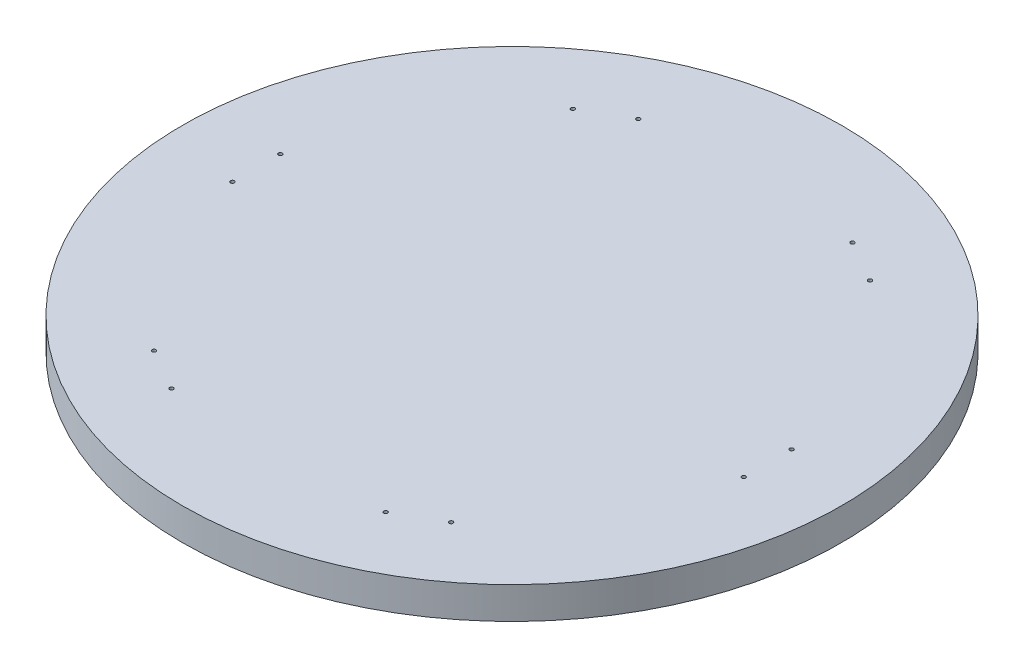
SolidWorks part; units mm, degrees
ref_plane "Front Plane" through (0, 0, 0) normal (0, 0, 1) x (1, 0, 0)
ref_plane "Top Plane" through (0, 0, 0) normal (0, 1, 0) x (1, 0, 0)
ref_plane "Right Plane" through (0, 0, 0) normal (1, 0, 0) x (0, 0, -1)
sketch "Sketch1" plane through (0, 0, 0) normal (0, 1, 0) x (1, 0, 0)
  circle A0 centre (0, 0) radius 261.9375
extrude "Boss-Extrude1" add sketch "Sketch1" along normal blind 25.4
sketch "Sketch6" plane through (0, 0, 0) normal (0, -1, 0) x (1, 0, 0)
  line L0 (203.2, 19.05) -> (203.2, -19.05) construction
  line L1 (215.9, 19.05) -> (215.9, -19.05)
  line L2 (190.5, 19.05) -> (190.5, -19.05)
  line L3 (203.2, -16.5451) -> (201.0307, -17.7976) construction
  line L4 (201.0307, -17.7976) -> (201.0307, -20.3024) construction
  line L5 (201.0307, -20.3024) -> (203.2, -21.5549) construction
  line L6 (203.2, -21.5549) -> (205.3693, -20.3024) construction
  line L7 (205.3693, -20.3024) -> (205.3693, -17.7976) construction
  line L8 (205.3693, -17.7976) -> (203.2, -16.5451) construction
  line L9 (203.2, 22.1294) -> (201.0307, 20.8769) construction
  line L10 (201.0307, 20.8769) -> (201.0307, 18.372) construction
  line L11 (201.0307, 18.372) -> (203.2, 17.1196) construction
  line L12 (203.2, 17.1196) -> (205.3693, 18.372) construction
  line L13 (205.3693, 18.372) -> (205.3693, 20.8769) construction
  line L14 (205.3693, 20.8769) -> (203.2, 22.1294) construction
  line L15 (0, 0) -> (203.2, 0) construction
  line L16 (87.2715, -184.2489) -> (85.1022, -182.9965) construction
  line L17 (85.1022, -182.9965) -> (82.9329, -184.2489) construction
  line L18 (82.9329, -184.2489) -> (82.9329, -186.7538) construction
  line L19 (82.9329, -186.7538) -> (85.1022, -188.0063) construction
  line L20 (85.1022, -188.0063) -> (87.2715, -186.7538) construction
  line L21 (87.2715, -186.7538) -> (87.2715, -184.2489) construction
  line L22 (120.7646, -164.9117) -> (118.5953, -163.6592) construction
  line L23 (118.5953, -163.6592) -> (116.426, -164.9117) construction
  line L24 (116.426, -164.9117) -> (116.426, -167.4166) construction
  line L25 (116.426, -167.4166) -> (118.5953, -168.669) construction
  line L26 (118.5953, -168.669) -> (120.7646, -167.4166) construction
  line L27 (120.7646, -167.4166) -> (120.7646, -164.9117) construction
  line L28 (0, 0) -> (101.6, -175.9764) construction
  line L29 (118.0978, -166.4514) -> (85.1022, -185.5014) construction
  line L30 (124.4478, -177.4499) -> (91.4522, -196.4999)
  line L31 (111.7478, -155.4528) -> (78.7522, -174.5028)
  line L32 (-115.9285, -167.7038) -> (-115.9285, -165.1989) construction
  line L33 (-115.9285, -165.1989) -> (-118.0978, -163.9465) construction
  line L34 (-118.0978, -163.9465) -> (-120.2671, -165.1989) construction
  line L35 (-120.2671, -165.1989) -> (-120.2671, -167.7038) construction
  line L36 (-120.2671, -167.7038) -> (-118.0978, -168.9563) construction
  line L37 (-118.0978, -168.9563) -> (-115.9285, -167.7038) construction
  line L38 (-82.4354, -187.0411) -> (-82.4354, -184.5362) construction
  line L39 (-82.4354, -184.5362) -> (-84.6047, -183.2837) construction
  line L40 (-84.6047, -183.2837) -> (-86.774, -184.5362) construction
  line L41 (-86.774, -184.5362) -> (-86.774, -187.0411) construction
  line L42 (-86.774, -187.0411) -> (-84.6047, -188.2935) construction
  line L43 (-84.6047, -188.2935) -> (-82.4354, -187.0411) construction
  line L44 (0, 0) -> (-101.6, -175.9764) construction
  line L45 (-85.1022, -185.5014) -> (-118.0978, -166.4514) construction
  line L46 (-91.4522, -196.4999) -> (-124.4478, -177.4499)
  line L47 (-78.7522, -174.5028) -> (-111.7478, -155.4528)
  line L48 (-203.2, 16.5451) -> (-201.0307, 17.7976) construction
  line L49 (-201.0307, 17.7976) -> (-201.0307, 20.3024) construction
  line L50 (-201.0307, 20.3024) -> (-203.2, 21.5549) construction
  line L51 (-203.2, 21.5549) -> (-205.3693, 20.3024) construction
  line L52 (-205.3693, 20.3024) -> (-205.3693, 17.7976) construction
  line L53 (-205.3693, 17.7976) -> (-203.2, 16.5451) construction
  line L54 (-203.2, -22.1294) -> (-201.0307, -20.8769) construction
  line L55 (-201.0307, -20.8769) -> (-201.0307, -18.372) construction
  line L56 (-201.0307, -18.372) -> (-203.2, -17.1196) construction
  line L57 (-203.2, -17.1196) -> (-205.3693, -18.372) construction
  line L58 (-205.3693, -18.372) -> (-205.3693, -20.8769) construction
  line L59 (-205.3693, -20.8769) -> (-203.2, -22.1294) construction
  line L60 (0, 0) -> (-203.2, 0) construction
  line L61 (-203.2, -19.05) -> (-203.2, 19.05) construction
  line L62 (-215.9, -19.05) -> (-215.9, 19.05)
  line L63 (-190.5, -19.05) -> (-190.5, 19.05)
  line L64 (-87.2715, 184.2489) -> (-85.1022, 182.9965) construction
  line L65 (-85.1022, 182.9965) -> (-82.9329, 184.2489) construction
  line L66 (-82.9329, 184.2489) -> (-82.9329, 186.7538) construction
  line L67 (-82.9329, 186.7538) -> (-85.1022, 188.0063) construction
  line L68 (-85.1022, 188.0063) -> (-87.2715, 186.7538) construction
  line L69 (-87.2715, 186.7538) -> (-87.2715, 184.2489) construction
  line L70 (-120.7646, 164.9117) -> (-118.5953, 163.6592) construction
  line L71 (-118.5953, 163.6592) -> (-116.426, 164.9117) construction
  line L72 (-116.426, 164.9117) -> (-116.426, 167.4166) construction
  line L73 (-116.426, 167.4166) -> (-118.5953, 168.669) construction
  line L74 (-118.5953, 168.669) -> (-120.7646, 167.4166) construction
  line L75 (-120.7646, 167.4166) -> (-120.7646, 164.9117) construction
  line L76 (0, 0) -> (-101.6, 175.9764) construction
  line L77 (-118.0978, 166.4514) -> (-85.1022, 185.5014) construction
  line L78 (-124.4478, 177.4499) -> (-91.4522, 196.4999)
  line L79 (-111.7478, 155.4528) -> (-78.7522, 174.5028)
  line L80 (115.9285, 167.7038) -> (115.9285, 165.1989) construction
  line L81 (115.9285, 165.1989) -> (118.0978, 163.9465) construction
  line L82 (118.0978, 163.9465) -> (120.2671, 165.1989) construction
  line L83 (120.2671, 165.1989) -> (120.2671, 167.7038) construction
  line L84 (120.2671, 167.7038) -> (118.0978, 168.9563) construction
  line L85 (118.0978, 168.9563) -> (115.9285, 167.7038) construction
  line L86 (82.4354, 187.0411) -> (82.4354, 184.5362) construction
  line L87 (82.4354, 184.5362) -> (84.6047, 183.2837) construction
  line L88 (84.6047, 183.2837) -> (86.774, 184.5362) construction
  line L89 (86.774, 184.5362) -> (86.774, 187.0411) construction
  line L90 (86.774, 187.0411) -> (84.6047, 188.2935) construction
  line L91 (84.6047, 188.2935) -> (82.4354, 187.0411) construction
  line L92 (0, 0) -> (101.6, 175.9764) construction
  line L93 (85.1022, 185.5014) -> (118.0978, 166.4514) construction
  line L94 (91.4522, 196.4999) -> (124.4478, 177.4499)
  line L95 (78.7522, 174.5028) -> (111.7478, 155.4528)
  arc A0 (215.9, 19.05) -> (190.5, 19.05) centre (203.2, 19.05) ccw
  arc A1 (190.5, -19.05) -> (215.9, -19.05) centre (203.2, -19.05) ccw
  circle A2 centre (203.2, -19.05) radius 2.1693 construction
  circle A3 centre (203.2, 19.6245) radius 2.1693 construction
  circle A4 centre (203.2, -19.05) radius 1.524 construction
  circle A5 centre (203.2, 19.6245) radius 1.524 construction
  circle A6 centre (85.1022, -185.5014) radius 2.1693 construction
  circle A7 centre (118.5953, -166.1641) radius 2.1693 construction
  circle A8 centre (85.1022, -185.5014) radius 1.524 construction
  circle A9 centre (118.5953, -166.1641) radius 1.524 construction
  arc A10 (124.4478, -177.4499) -> (111.7478, -155.4528) centre (118.0978, -166.4514) ccw
  arc A11 (78.7522, -174.5028) -> (91.4522, -196.4999) centre (85.1022, -185.5014) ccw
  circle A12 centre (-118.0978, -166.4514) radius 2.1693 construction
  circle A13 centre (-84.6047, -185.7886) radius 2.1693 construction
  circle A14 centre (-118.0978, -166.4514) radius 1.524 construction
  circle A15 centre (-84.6047, -185.7886) radius 1.524 construction
  arc A16 (-91.4522, -196.4999) -> (-78.7522, -174.5028) centre (-85.1022, -185.5014) ccw
  arc A17 (-111.7478, -155.4528) -> (-124.4478, -177.4499) centre (-118.0978, -166.4514) ccw
  circle A18 centre (-203.2, 19.05) radius 2.1693 construction
  circle A19 centre (-203.2, -19.6245) radius 2.1693 construction
  circle A20 centre (-203.2, 19.05) radius 1.524 construction
  circle A21 centre (-203.2, -19.6245) radius 1.524 construction
  arc A22 (-215.9, -19.05) -> (-190.5, -19.05) centre (-203.2, -19.05) ccw
  arc A23 (-190.5, 19.05) -> (-215.9, 19.05) centre (-203.2, 19.05) ccw
  circle A24 centre (-85.1022, 185.5014) radius 2.1693 construction
  circle A25 centre (-118.5953, 166.1641) radius 2.1693 construction
  circle A26 centre (-85.1022, 185.5014) radius 1.524 construction
  circle A27 centre (-118.5953, 166.1641) radius 1.524 construction
  arc A28 (-124.4478, 177.4499) -> (-111.7478, 155.4528) centre (-118.0978, 166.4514) ccw
  arc A29 (-78.7522, 174.5028) -> (-91.4522, 196.4999) centre (-85.1022, 185.5014) ccw
  circle A30 centre (118.0978, 166.4514) radius 2.1693 construction
  circle A31 centre (84.6047, 185.7886) radius 2.1693 construction
  circle A32 centre (118.0978, 166.4514) radius 1.524 construction
  circle A33 centre (84.6047, 185.7886) radius 1.524 construction
  arc A34 (91.4522, 196.4999) -> (78.7522, 174.5028) centre (85.1022, 185.5014) ccw
  arc A35 (111.7478, 155.4528) -> (124.4478, 177.4499) centre (118.0978, 166.4514) ccw
  point P2 (203.2, 0)
  point P32 (101.6, -175.9764)
  point P58 (-101.6, -175.9764)
  point P84 (-203.2, 0)
  point P110 (-101.6, 175.9764)
  point P136 (101.6, 175.9764)
  point P160 (0, 0)
  dimension "D1" = 6
extrude "Cut-Extrude4" cut sketch "Sketch6" against normal blind 12.7
sketch "Sketch9" plane through (0, 0, 0) normal (0, -1, 0) x (1, 0, 0)
  circle A0 centre (0, 0) radius 25.4
extrude "Boss-Extrude2" add sketch "Sketch9" along normal blind 10.16 and the other way through all
sketch "Sketch10" plane through (0, -10.16, 0) normal (0, -1, 0) x (1, 0, 0)
  line L0 (0, -2.032) -> (0, 1.524) construction
  line L1 (-1.344, 1.524) -> (1.344, 1.524)
  line L2 (-2.032, 0) -> (-2.032, 1.524)
  line L3 (-2.032, 1.524) -> (-1.344, 1.524)
  line L4 (2.032, 0) -> (2.032, 1.524)
  line L5 (2.032, 1.524) -> (1.344, 1.524)
  arc A0 (-2.032, 0) -> (2.032, 0) centre (0, 0) ccw
extrude "Cut-Extrude7" cut sketch "Sketch10" against normal blind 19.05
sketch "Sketch11" plane through (0, 0, 0) normal (0, -1, 0) x (1, 0, 0)
  line L0 (0, 0) -> (-11.1642, -177.4492) construction
  line L1 (0, 0) -> (0, -291.8902) construction
  line L2 (0, 0) -> (11.1642, -177.4492) construction
  line L3 (-33.3164, -174.6507) -> (-22.2403, -176.0499) construction
  line L4 (-11.1642, -177.4492) -> (0, -177.4492) construction
  line L5 (0, -177.4492) -> (11.1642, -177.4492) construction
  line L6 (-22.2403, -176.0499) -> (-11.1642, -177.4492) construction
  line L7 (-54.9432, -169.0978) -> (-44.1298, -171.8743) construction
  line L8 (-44.1298, -171.8743) -> (-33.3164, -174.6507) construction
  line L9 (-75.7036, -160.8782) -> (-65.3234, -164.988) construction
  line L10 (-65.3234, -164.988) -> (-54.9432, -169.0978) construction
  line L11 (-95.27, -150.1215) -> (-85.4868, -155.4999) construction
  line L12 (-85.4868, -155.4999) -> (-75.7036, -160.8782) construction
  line L13 (-113.334, -136.9973) -> (-104.302, -143.5594) construction
  line L14 (-104.302, -143.5594) -> (-95.27, -150.1215) construction
  line L15 (-129.6106, -121.7125) -> (-121.4723, -129.3549) construction
  line L16 (-121.4723, -129.3549) -> (-113.334, -136.9973) construction
  line L17 (-143.8432, -104.5082) -> (-136.7269, -113.1103) construction
  line L18 (-136.7269, -113.1103) -> (-129.6106, -121.7125) construction
  line L19 (-155.8073, -85.6558) -> (-149.8253, -95.082) construction
  line L20 (-149.8253, -95.082) -> (-143.8432, -104.5082) construction
  line L21 (-165.3143, -65.4525) -> (-160.5608, -75.5542) construction
  line L22 (-160.5608, -75.5542) -> (-155.8073, -85.6558) construction
  line L23 (-172.2141, -44.2171) -> (-168.7642, -54.8348) construction
  line L24 (-168.7642, -54.8348) -> (-165.3143, -65.4525) construction
  line L25 (-176.398, -22.2842) -> (-174.306, -33.2507) construction
  line L26 (-174.306, -33.2507) -> (-172.2141, -44.2171) construction
  line L27 (-177.8, 0) -> (-177.099, -11.1421) construction
  line L28 (-177.099, -11.1421) -> (-176.398, -22.2842) construction
  line L29 (-176.398, 22.2842) -> (-177.099, 11.1421) construction
  line L30 (-177.099, 11.1421) -> (-177.8, 0) construction
  line L31 (-172.2141, 44.2171) -> (-174.306, 33.2507) construction
  line L32 (-174.306, 33.2507) -> (-176.398, 22.2842) construction
  line L33 (-165.3143, 65.4525) -> (-168.7642, 54.8348) construction
  line L34 (-168.7642, 54.8348) -> (-172.2141, 44.2171) construction
  line L35 (-155.8073, 85.6558) -> (-160.5608, 75.5542) construction
  line L36 (-160.5608, 75.5542) -> (-165.3143, 65.4525) construction
  line L37 (-143.8432, 104.5082) -> (-149.8253, 95.082) construction
  line L38 (-149.8253, 95.082) -> (-155.8073, 85.6558) construction
  line L39 (-129.6106, 121.7125) -> (-136.7269, 113.1103) construction
  line L40 (-136.7269, 113.1103) -> (-143.8432, 104.5082) construction
  line L41 (-113.334, 136.9973) -> (-121.4723, 129.3549) construction
  line L42 (-121.4723, 129.3549) -> (-129.6106, 121.7125) construction
  line L43 (-95.27, 150.1215) -> (-104.302, 143.5594) construction
  line L44 (-104.302, 143.5594) -> (-113.334, 136.9973) construction
  line L45 (-75.7036, 160.8782) -> (-85.4868, 155.4999) construction
  line L46 (-85.4868, 155.4999) -> (-95.27, 150.1215) construction
  line L47 (-54.9432, 169.0978) -> (-65.3234, 164.988) construction
  line L48 (-65.3234, 164.988) -> (-75.7036, 160.8782) construction
  line L49 (-33.3164, 174.6507) -> (-44.1298, 171.8743) construction
  line L50 (-44.1298, 171.8743) -> (-54.9432, 169.0978) construction
  line L51 (-11.1642, 177.4492) -> (-22.2403, 176.0499) construction
  line L52 (-22.2403, 176.0499) -> (-33.3164, 174.6507) construction
  line L53 (11.1642, 177.4492) -> (0, 177.4492) construction
  line L54 (0, 177.4492) -> (-11.1642, 177.4492) construction
  line L55 (33.3164, 174.6507) -> (22.2403, 176.0499) construction
  line L56 (22.2403, 176.0499) -> (11.1642, 177.4492) construction
  line L57 (54.9432, 169.0978) -> (44.1298, 171.8743) construction
  line L58 (44.1298, 171.8743) -> (33.3164, 174.6507) construction
  line L59 (75.7036, 160.8782) -> (65.3234, 164.988) construction
  line L60 (65.3234, 164.988) -> (54.9432, 169.0978) construction
  line L61 (95.27, 150.1215) -> (85.4868, 155.4999) construction
  line L62 (85.4868, 155.4999) -> (75.7036, 160.8782) construction
  line L63 (113.334, 136.9973) -> (104.302, 143.5594) construction
  line L64 (104.302, 143.5594) -> (95.27, 150.1215) construction
  line L65 (129.6106, 121.7125) -> (121.4723, 129.3549) construction
  line L66 (121.4723, 129.3549) -> (113.334, 136.9973) construction
  line L67 (143.8432, 104.5082) -> (136.7269, 113.1103) construction
  line L68 (136.7269, 113.1103) -> (129.6106, 121.7125) construction
  line L69 (155.8073, 85.6558) -> (149.8253, 95.082) construction
  line L70 (149.8253, 95.082) -> (143.8432, 104.5082) construction
  line L71 (165.3143, 65.4525) -> (160.5608, 75.5542) construction
  line L72 (160.5608, 75.5542) -> (155.8073, 85.6558) construction
  line L73 (172.2141, 44.2171) -> (168.7642, 54.8348) construction
  line L74 (168.7642, 54.8348) -> (165.3143, 65.4525) construction
  line L75 (176.398, 22.2842) -> (174.306, 33.2507) construction
  line L76 (174.306, 33.2507) -> (172.2141, 44.2171) construction
  line L77 (177.8, 0) -> (177.099, 11.1421) construction
  line L78 (177.099, 11.1421) -> (176.398, 22.2842) construction
  line L79 (176.398, -22.2842) -> (177.099, -11.1421) construction
  line L80 (177.099, -11.1421) -> (177.8, 0) construction
  line L81 (172.2141, -44.2171) -> (174.306, -33.2507) construction
  line L82 (174.306, -33.2507) -> (176.398, -22.2842) construction
  line L83 (165.3143, -65.4525) -> (168.7642, -54.8348) construction
  line L84 (168.7642, -54.8348) -> (172.2141, -44.2171) construction
  line L85 (155.8073, -85.6558) -> (160.5608, -75.5542) construction
  line L86 (160.5608, -75.5542) -> (165.3143, -65.4525) construction
  line L87 (143.8432, -104.5082) -> (149.8253, -95.082) construction
  line L88 (149.8253, -95.082) -> (155.8073, -85.6558) construction
  line L89 (129.6106, -121.7125) -> (136.7269, -113.1103) construction
  line L90 (136.7269, -113.1103) -> (143.8432, -104.5082) construction
  line L91 (113.334, -136.9973) -> (121.4723, -129.3549) construction
  line L92 (121.4723, -129.3549) -> (129.6106, -121.7125) construction
  line L93 (95.27, -150.1215) -> (104.302, -143.5594) construction
  line L94 (104.302, -143.5594) -> (113.334, -136.9973) construction
  line L95 (75.7036, -160.8782) -> (85.4868, -155.4999) construction
  line L96 (85.4868, -155.4999) -> (95.27, -150.1215) construction
  line L97 (54.9432, -169.0978) -> (65.3234, -164.988) construction
  line L98 (65.3234, -164.988) -> (75.7036, -160.8782) construction
  line L99 (33.3164, -174.6507) -> (44.1298, -171.8743) construction
  line L100 (44.1298, -171.8743) -> (54.9432, -169.0978) construction
  line L101 (11.1642, -177.4492) -> (22.2403, -176.0499) construction
  line L102 (22.2403, -176.0499) -> (33.3164, -174.6507) construction
  circle A0 centre (0, 0) radius 177.8 construction
  arc A1 (0, -177.4492) -> (-11.1201, -176.7495) centre (-5.5821, -177.4492) ccw
  arc A2 (0, -177.4492) -> (11.1201, -176.7495) centre (5.5821, -177.4492) ccw
  arc A3 (-22.2403, -176.0499) -> (-33.185, -173.9621) centre (-27.7783, -175.3503) ccw
  arc A4 (-22.2403, -176.0499) -> (-11.1201, -176.7495) centre (-16.7022, -176.7495) ccw
  arc A5 (-44.1298, -171.8743) -> (-54.7266, -168.4312) centre (-49.5365, -170.4861) ccw
  arc A6 (-44.1298, -171.8743) -> (-33.185, -173.9621) centre (-38.7231, -173.2625) ccw
  arc A7 (-65.3234, -164.988) -> (-75.4051, -160.244) centre (-70.5135, -162.9331) ccw
  arc A8 (-65.3234, -164.988) -> (-54.7266, -168.4312) centre (-60.1333, -167.0429) ccw
  arc A9 (-85.4868, -155.4999) -> (-94.8944, -149.5296) centre (-90.3784, -152.8107) ccw
  arc A10 (-85.4868, -155.4999) -> (-75.4051, -160.244) centre (-80.5952, -158.1891) ccw
  arc A11 (-104.302, -143.5594) -> (-112.8871, -136.4571) centre (-108.818, -140.2783) ccw
  arc A12 (-104.302, -143.5594) -> (-94.8944, -149.5296) centre (-99.786, -146.8404) ccw
  arc A13 (-121.4723, -129.3549) -> (-129.0996, -121.2326) centre (-125.5415, -125.5337) ccw
  arc A14 (-121.4723, -129.3549) -> (-112.8871, -136.4571) centre (-117.4031, -133.1761) ccw
  arc A15 (-136.7269, -113.1103) -> (-143.2761, -104.0962) centre (-140.2851, -108.8093) ccw
  arc A16 (-136.7269, -113.1103) -> (-129.0996, -121.2326) centre (-133.1688, -117.4114) ccw
  arc A17 (-149.8253, -95.082) -> (-155.193, -85.3181) centre (-152.8163, -90.3689) ccw
  arc A18 (-149.8253, -95.082) -> (-143.2761, -104.0962) centre (-146.8342, -99.7951) ccw
  arc A19 (-160.5608, -75.5542) -> (-164.6625, -65.1945) centre (-162.9375, -70.5034) ccw
  arc A20 (-160.5608, -75.5542) -> (-155.193, -85.3181) centre (-158.1841, -80.605) ccw
  arc A21 (-168.7642, -54.8348) -> (-171.5351, -44.0427) centre (-170.4891, -49.5259) ccw
  arc A22 (-168.7642, -54.8348) -> (-164.6625, -65.1945) centre (-167.0392, -60.1437) ccw
  arc A23 (-174.306, -33.2507) -> (-175.7025, -22.1964) centre (-175.352, -27.7675) ccw
  arc A24 (-174.306, -33.2507) -> (-171.5351, -44.0427) centre (-173.2601, -38.7339) ccw
  arc A25 (-177.099, -11.1421) -> (-177.099, 0) centre (-177.4495, -5.5711) ccw
  arc A26 (-177.099, -11.1421) -> (-175.7025, -22.1964) centre (-176.7485, -16.7132) ccw
  arc A27 (-177.099, 11.1421) -> (-175.7025, 22.1964) centre (-176.7485, 16.7132) ccw
  arc A28 (-177.099, 11.1421) -> (-177.099, 0) centre (-177.4495, 5.5711) ccw
  arc A29 (-174.306, 33.2507) -> (-171.5351, 44.0427) centre (-173.2601, 38.7339) ccw
  arc A30 (-174.306, 33.2507) -> (-175.7025, 22.1964) centre (-175.352, 27.7675) ccw
  arc A31 (-168.7642, 54.8348) -> (-164.6625, 65.1945) centre (-167.0392, 60.1437) ccw
  arc A32 (-168.7642, 54.8348) -> (-171.5351, 44.0427) centre (-170.4891, 49.5259) ccw
  arc A33 (-160.5608, 75.5542) -> (-155.193, 85.3181) centre (-158.1841, 80.605) ccw
  arc A34 (-160.5608, 75.5542) -> (-164.6625, 65.1945) centre (-162.9375, 70.5034) ccw
  arc A35 (-149.8253, 95.082) -> (-143.2761, 104.0962) centre (-146.8342, 99.7951) ccw
  arc A36 (-149.8253, 95.082) -> (-155.193, 85.3181) centre (-152.8163, 90.3689) ccw
  arc A37 (-136.7269, 113.1103) -> (-129.0996, 121.2326) centre (-133.1688, 117.4114) ccw
  arc A38 (-136.7269, 113.1103) -> (-143.2761, 104.0962) centre (-140.2851, 108.8093) ccw
  arc A39 (-121.4723, 129.3549) -> (-112.8871, 136.4571) centre (-117.4031, 133.1761) ccw
  arc A40 (-121.4723, 129.3549) -> (-129.0996, 121.2326) centre (-125.5415, 125.5337) ccw
  arc A41 (-104.302, 143.5594) -> (-94.8944, 149.5296) centre (-99.786, 146.8404) ccw
  arc A42 (-104.302, 143.5594) -> (-112.8871, 136.4571) centre (-108.818, 140.2783) ccw
  arc A43 (-85.4868, 155.4999) -> (-75.4051, 160.244) centre (-80.5952, 158.1891) ccw
  arc A44 (-85.4868, 155.4999) -> (-94.8944, 149.5296) centre (-90.3784, 152.8107) ccw
  arc A45 (-65.3234, 164.988) -> (-54.7266, 168.4312) centre (-60.1333, 167.0429) ccw
  arc A46 (-65.3234, 164.988) -> (-75.4051, 160.244) centre (-70.5135, 162.9331) ccw
  arc A47 (-44.1298, 171.8743) -> (-33.185, 173.9621) centre (-38.7231, 173.2625) ccw
  arc A48 (-44.1298, 171.8743) -> (-54.7266, 168.4312) centre (-49.5365, 170.4861) ccw
  arc A49 (-22.2403, 176.0499) -> (-11.1201, 176.7495) centre (-16.7022, 176.7495) ccw
  arc A50 (-22.2403, 176.0499) -> (-33.185, 173.9621) centre (-27.7783, 175.3503) ccw
  arc A51 (0, 177.4492) -> (11.1201, 176.7495) centre (5.5821, 177.4492) ccw
  arc A52 (0, 177.4492) -> (-11.1201, 176.7495) centre (-5.5821, 177.4492) ccw
  arc A53 (22.2403, 176.0499) -> (33.185, 173.9621) centre (27.7783, 175.3503) ccw
  arc A54 (22.2403, 176.0499) -> (11.1201, 176.7495) centre (16.7022, 176.7495) ccw
  arc A55 (44.1298, 171.8743) -> (54.7266, 168.4312) centre (49.5365, 170.4861) ccw
  arc A56 (44.1298, 171.8743) -> (33.185, 173.9621) centre (38.7231, 173.2625) ccw
  arc A57 (65.3234, 164.988) -> (75.4051, 160.244) centre (70.5135, 162.9331) ccw
  arc A58 (65.3234, 164.988) -> (54.7266, 168.4312) centre (60.1333, 167.0429) ccw
  arc A59 (85.4868, 155.4999) -> (94.8944, 149.5296) centre (90.3784, 152.8107) ccw
  arc A60 (85.4868, 155.4999) -> (75.4051, 160.244) centre (80.5952, 158.1891) ccw
  arc A61 (104.302, 143.5594) -> (112.8871, 136.4571) centre (108.818, 140.2783) ccw
  arc A62 (104.302, 143.5594) -> (94.8944, 149.5296) centre (99.786, 146.8404) ccw
  arc A63 (121.4723, 129.3549) -> (129.0996, 121.2326) centre (125.5415, 125.5337) ccw
  arc A64 (121.4723, 129.3549) -> (112.8871, 136.4571) centre (117.4031, 133.1761) ccw
  arc A65 (136.7269, 113.1103) -> (143.2761, 104.0962) centre (140.2851, 108.8093) ccw
  arc A66 (136.7269, 113.1103) -> (129.0996, 121.2326) centre (133.1688, 117.4114) ccw
  arc A67 (149.8253, 95.082) -> (155.193, 85.3181) centre (152.8163, 90.3689) ccw
  arc A68 (149.8253, 95.082) -> (143.2761, 104.0962) centre (146.8342, 99.7951) ccw
  arc A69 (160.5608, 75.5542) -> (164.6625, 65.1945) centre (162.9375, 70.5034) ccw
  arc A70 (160.5608, 75.5542) -> (155.193, 85.3181) centre (158.1841, 80.605) ccw
  arc A71 (168.7642, 54.8348) -> (171.5351, 44.0427) centre (170.4891, 49.5259) ccw
  arc A72 (168.7642, 54.8348) -> (164.6625, 65.1945) centre (167.0392, 60.1437) ccw
  arc A73 (174.306, 33.2507) -> (175.7025, 22.1964) centre (175.352, 27.7675) ccw
  arc A74 (174.306, 33.2507) -> (171.5351, 44.0427) centre (173.2601, 38.7339) ccw
  arc A75 (177.099, 11.1421) -> (177.099, 0) centre (177.4495, 5.5711) ccw
  arc A76 (177.099, 11.1421) -> (175.7025, 22.1964) centre (176.7485, 16.7132) ccw
  arc A77 (177.099, -11.1421) -> (175.7025, -22.1964) centre (176.7485, -16.7132) ccw
  arc A78 (177.099, -11.1421) -> (177.099, 0) centre (177.4495, -5.5711) ccw
  arc A79 (174.306, -33.2507) -> (171.5351, -44.0427) centre (173.2601, -38.7339) ccw
  arc A80 (174.306, -33.2507) -> (175.7025, -22.1964) centre (175.352, -27.7675) ccw
  arc A81 (168.7642, -54.8348) -> (164.6625, -65.1945) centre (167.0392, -60.1437) ccw
  arc A82 (168.7642, -54.8348) -> (171.5351, -44.0427) centre (170.4891, -49.5259) ccw
  arc A83 (160.5608, -75.5542) -> (155.193, -85.3181) centre (158.1841, -80.605) ccw
  arc A84 (160.5608, -75.5542) -> (164.6625, -65.1945) centre (162.9375, -70.5034) ccw
  arc A85 (149.8253, -95.082) -> (143.2761, -104.0962) centre (146.8342, -99.7951) ccw
  arc A86 (149.8253, -95.082) -> (155.193, -85.3181) centre (152.8163, -90.3689) ccw
  arc A87 (136.7269, -113.1103) -> (129.0996, -121.2326) centre (133.1688, -117.4114) ccw
  arc A88 (136.7269, -113.1103) -> (143.2761, -104.0962) centre (140.2851, -108.8093) ccw
  arc A89 (121.4723, -129.3549) -> (112.8871, -136.4571) centre (117.4031, -133.1761) ccw
  arc A90 (121.4723, -129.3549) -> (129.0996, -121.2326) centre (125.5415, -125.5337) ccw
  arc A91 (104.302, -143.5594) -> (94.8944, -149.5296) centre (99.786, -146.8404) ccw
  arc A92 (104.302, -143.5594) -> (112.8871, -136.4571) centre (108.818, -140.2783) ccw
  arc A93 (85.4868, -155.4999) -> (75.4051, -160.244) centre (80.5952, -158.1891) ccw
  arc A94 (85.4868, -155.4999) -> (94.8944, -149.5296) centre (90.3784, -152.8107) ccw
  arc A95 (65.3234, -164.988) -> (54.7266, -168.4312) centre (60.1333, -167.0429) ccw
  arc A96 (65.3234, -164.988) -> (75.4051, -160.244) centre (70.5135, -162.9331) ccw
  arc A97 (44.1298, -171.8743) -> (33.185, -173.9621) centre (38.7231, -173.2625) ccw
  arc A98 (44.1298, -171.8743) -> (54.7266, -168.4312) centre (49.5365, -170.4861) ccw
  arc A99 (22.2403, -176.0499) -> (11.1201, -176.7495) centre (16.7022, -176.7495) ccw
  arc A100 (22.2403, -176.0499) -> (33.185, -173.9621) centre (27.7783, -175.3503) ccw
  circle A101 centre (0, 0) radius 27.7675
  point P356 (0, 0)
  dimension "D1" = 50
extrude "Cut-Extrude9" cut sketch "Sketch11" against normal blind 6.35
sketch "Sketch12" plane through (0, 12.7, 0) normal (0, -1, 0) x (1, 0, 0)
  line L0 (203.2, 19.05) -> (203.2, -19.05) construction
  line L1 (215.9, 19.05) -> (215.9, -19.05) construction
  line L2 (190.5, 19.05) -> (190.5, -19.05) construction
  line L3 (203.2, -16.5451) -> (201.0307, -17.7975) construction
  line L4 (201.0307, -17.7975) -> (201.0307, -20.3024) construction
  line L5 (201.0307, -20.3024) -> (203.2, -21.5549) construction
  line L6 (203.2, -21.5549) -> (205.3693, -20.3024) construction
  line L7 (205.3693, -20.3024) -> (205.3693, -17.7975) construction
  line L8 (205.3693, -17.7975) -> (203.2, -16.5451) construction
  line L9 (203.2, 21.5549) -> (201.0307, 20.3025) construction
  line L10 (201.0307, 20.3025) -> (201.0307, 17.7976) construction
  line L11 (201.0307, 17.7976) -> (203.2, 16.5451) construction
  line L12 (203.2, 16.5451) -> (205.3693, 17.7976) construction
  line L13 (205.3693, 17.7976) -> (205.3693, 20.3025) construction
  line L14 (205.3693, 20.3025) -> (203.2, 21.5549) construction
  line L15 (190.5, -19.05) -> (203.2, -19.05) construction
  line L16 (87.2715, -184.2489) -> (85.1022, -182.9965) construction
  line L17 (85.1022, -182.9965) -> (82.9329, -184.2489) construction
  line L18 (82.9329, -184.2489) -> (82.9329, -186.7538) construction
  line L19 (82.9329, -186.7538) -> (85.1022, -188.0062) construction
  line L20 (85.1022, -188.0062) -> (87.2715, -186.7538) construction
  line L21 (87.2715, -186.7538) -> (87.2715, -184.2489) construction
  line L22 (120.2671, -165.1989) -> (118.0978, -163.9465) construction
  line L23 (118.0978, -163.9465) -> (115.9285, -165.1989) construction
  line L24 (115.9285, -165.1989) -> (115.9285, -167.7038) construction
  line L25 (115.9285, -167.7038) -> (118.0978, -168.9562) construction
  line L26 (118.0978, -168.9562) -> (120.2671, -167.7038) construction
  line L27 (120.2671, -167.7038) -> (120.2671, -165.1989) construction
  line L28 (78.7522, -174.5028) -> (85.1022, -185.5014) construction
  line L29 (118.0978, -166.4514) -> (85.1022, -185.5014) construction
  line L30 (124.4478, -177.4499) -> (91.4522, -196.4999) construction
  line L31 (111.7478, -155.4528) -> (78.7522, -174.5028) construction
  line L32 (-115.9285, -167.7038) -> (-115.9285, -165.1989) construction
  line L33 (-115.9285, -165.1989) -> (-118.0978, -163.9465) construction
  line L34 (-118.0978, -163.9465) -> (-120.2671, -165.1989) construction
  line L35 (-120.2671, -165.1989) -> (-120.2671, -167.7038) construction
  line L36 (-120.2671, -167.7038) -> (-118.0978, -168.9563) construction
  line L37 (-118.0978, -168.9563) -> (-115.9285, -167.7038) construction
  line L38 (-82.9329, -186.7538) -> (-82.9329, -184.2489) construction
  line L39 (-82.9329, -184.2489) -> (-85.1022, -182.9965) construction
  line L40 (-85.1022, -182.9965) -> (-87.2715, -184.2489) construction
  line L41 (-87.2715, -184.2489) -> (-87.2715, -186.7538) construction
  line L42 (-87.2715, -186.7538) -> (-85.1022, -188.0063) construction
  line L43 (-85.1022, -188.0063) -> (-82.9329, -186.7538) construction
  line L44 (-111.7478, -155.4528) -> (-118.0978, -166.4514) construction
  line L45 (-85.1022, -185.5014) -> (-118.0978, -166.4514) construction
  line L46 (-91.4522, -196.4999) -> (-124.4478, -177.4499) construction
  line L47 (-78.7522, -174.5028) -> (-111.7478, -155.4528) construction
  line L48 (-203.2, 16.5451) -> (-201.0307, 17.7975) construction
  line L49 (-201.0307, 17.7975) -> (-201.0307, 20.3024) construction
  line L50 (-201.0307, 20.3024) -> (-203.2, 21.5549) construction
  line L51 (-203.2, 21.5549) -> (-205.3693, 20.3024) construction
  line L52 (-205.3693, 20.3024) -> (-205.3693, 17.7975) construction
  line L53 (-205.3693, 17.7975) -> (-203.2, 16.5451) construction
  line L54 (-203.2, -21.5549) -> (-201.0307, -20.3025) construction
  line L55 (-201.0307, -20.3025) -> (-201.0307, -17.7976) construction
  line L56 (-201.0307, -17.7976) -> (-203.2, -16.5451) construction
  line L57 (-203.2, -16.5451) -> (-205.3693, -17.7976) construction
  line L58 (-205.3693, -17.7976) -> (-205.3693, -20.3025) construction
  line L59 (-205.3693, -20.3025) -> (-203.2, -21.5549) construction
  line L60 (-190.5, 19.05) -> (-203.2, 19.05) construction
  line L61 (-203.2, -19.05) -> (-203.2, 19.05) construction
  line L62 (-215.9, -19.05) -> (-215.9, 19.05) construction
  line L63 (-190.5, -19.05) -> (-190.5, 19.05) construction
  line L64 (-87.2715, 184.2489) -> (-85.1022, 182.9965) construction
  line L65 (-85.1022, 182.9965) -> (-82.9329, 184.2489) construction
  line L66 (-82.9329, 184.2489) -> (-82.9329, 186.7538) construction
  line L67 (-82.9329, 186.7538) -> (-85.1022, 188.0062) construction
  line L68 (-85.1022, 188.0062) -> (-87.2715, 186.7538) construction
  line L69 (-87.2715, 186.7538) -> (-87.2715, 184.2489) construction
  line L70 (-120.2671, 165.1989) -> (-118.0978, 163.9465) construction
  line L71 (-118.0978, 163.9465) -> (-115.9285, 165.1989) construction
  line L72 (-115.9285, 165.1989) -> (-115.9285, 167.7038) construction
  line L73 (-115.9285, 167.7038) -> (-118.0978, 168.9562) construction
  line L74 (-118.0978, 168.9562) -> (-120.2671, 167.7038) construction
  line L75 (-120.2671, 167.7038) -> (-120.2671, 165.1989) construction
  line L76 (-78.7522, 174.5028) -> (-85.1022, 185.5014) construction
  line L77 (-118.0978, 166.4514) -> (-85.1022, 185.5014) construction
  line L78 (-124.4478, 177.4499) -> (-91.4522, 196.4999) construction
  line L79 (-111.7478, 155.4528) -> (-78.7522, 174.5028) construction
  line L80 (115.9285, 167.7038) -> (115.9285, 165.1989) construction
  line L81 (115.9285, 165.1989) -> (118.0978, 163.9465) construction
  line L82 (118.0978, 163.9465) -> (120.2671, 165.1989) construction
  line L83 (120.2671, 165.1989) -> (120.2671, 167.7038) construction
  line L84 (120.2671, 167.7038) -> (118.0978, 168.9563) construction
  line L85 (118.0978, 168.9563) -> (115.9285, 167.7038) construction
  line L86 (82.9329, 186.7538) -> (82.9329, 184.2489) construction
  line L87 (82.9329, 184.2489) -> (85.1022, 182.9965) construction
  line L88 (85.1022, 182.9965) -> (87.2715, 184.2489) construction
  line L89 (87.2715, 184.2489) -> (87.2715, 186.7538) construction
  line L90 (87.2715, 186.7538) -> (85.1022, 188.0063) construction
  line L91 (85.1022, 188.0063) -> (82.9329, 186.7538) construction
  line L92 (111.7478, 155.4528) -> (118.0978, 166.4514) construction
  line L93 (85.1022, 185.5014) -> (118.0978, 166.4514) construction
  line L94 (91.4522, 196.4999) -> (124.4478, 177.4499) construction
  line L95 (78.7522, 174.5028) -> (111.7478, 155.4528) construction
  line L96 (0, 0) -> (-101.6, 175.9764) construction
  arc A0 (215.9, 19.05) -> (190.5, 19.05) centre (203.2, 19.05) ccw construction
  arc A1 (190.5, -19.05) -> (215.9, -19.05) centre (203.2, -19.05) ccw construction
  circle A2 centre (203.2, -19.05) radius 2.1693 construction
  circle A3 centre (203.2, 19.05) radius 2.1693 construction
  circle A4 centre (203.2, -19.05) radius 1.524
  circle A5 centre (203.2, 19.05) radius 1.524
  circle A6 centre (85.1022, -185.5014) radius 1.524
  circle A7 centre (118.0978, -166.4514) radius 1.524
  circle A8 centre (85.1022, -185.5014) radius 2.1693 construction
  circle A9 centre (118.0978, -166.4514) radius 2.1693 construction
  arc A10 (124.4478, -177.4499) -> (111.7478, -155.4528) centre (118.0978, -166.4514) ccw construction
  arc A11 (78.7522, -174.5028) -> (91.4522, -196.4999) centre (85.1022, -185.5014) ccw construction
  circle A12 centre (-118.0978, -166.4514) radius 1.524
  circle A13 centre (-85.1022, -185.5014) radius 1.524
  circle A14 centre (-118.0978, -166.4514) radius 2.1693 construction
  circle A15 centre (-85.1022, -185.5014) radius 2.1693 construction
  arc A16 (-91.4522, -196.4999) -> (-78.7522, -174.5028) centre (-85.1022, -185.5014) ccw construction
  arc A17 (-111.7478, -155.4528) -> (-124.4478, -177.4499) centre (-118.0978, -166.4514) ccw construction
  circle A18 centre (-203.2, 19.05) radius 1.524
  circle A19 centre (-203.2, -19.05) radius 1.524
  circle A20 centre (-203.2, 19.05) radius 2.1693 construction
  circle A21 centre (-203.2, -19.05) radius 2.1693 construction
  arc A22 (-215.9, -19.05) -> (-190.5, -19.05) centre (-203.2, -19.05) ccw construction
  arc A23 (-190.5, 19.05) -> (-215.9, 19.05) centre (-203.2, 19.05) ccw construction
  circle A24 centre (-85.1022, 185.5014) radius 1.524
  circle A25 centre (-118.0978, 166.4514) radius 1.524
  circle A26 centre (-85.1022, 185.5014) radius 2.1693 construction
  circle A27 centre (-118.0978, 166.4514) radius 2.1693 construction
  arc A28 (-124.4478, 177.4499) -> (-111.7478, 155.4528) centre (-118.0978, 166.4514) ccw construction
  arc A29 (-78.7522, 174.5028) -> (-91.4522, 196.4999) centre (-85.1022, 185.5014) ccw construction
  circle A30 centre (118.0978, 166.4514) radius 1.524
  circle A31 centre (85.1022, 185.5014) radius 1.524
  circle A32 centre (118.0978, 166.4514) radius 2.1693 construction
  circle A33 centre (85.1022, 185.5014) radius 2.1693 construction
  arc A34 (91.4522, 196.4999) -> (78.7522, 174.5028) centre (85.1022, 185.5014) ccw construction
  arc A35 (111.7478, 155.4528) -> (124.4478, 177.4499) centre (118.0978, 166.4514) ccw construction
  point P2 (203.2, 0)
  point P29 (101.6, -175.9764)
  point P56 (-101.6, -175.9764)
  point P83 (-203.2, 0)
  point P110 (-101.6, 175.9764)
  point P137 (101.6, 175.9764)
  point P162 (0, 0)
extrude "Cut-Extrude10" cut sketch "Sketch12" against normal through all
sketch "Sketch13" plane through (0, 0, 0) normal (0, -1, 0) x (1, 0, 0)
  line L3 (-33.3164, -174.6507) -> (-22.2403, -176.0499) construction
  line L4 (-11.1642, -177.4492) -> (0, -177.4492) construction
  line L5 (0, -177.4492) -> (11.1642, -177.4492) construction
  line L6 (-22.2403, -176.0499) -> (-11.1642, -177.4492) construction
  line L7 (-54.9432, -169.0978) -> (-44.1298, -171.8743) construction
  line L8 (-44.1298, -171.8743) -> (-33.3164, -174.6507) construction
  line L9 (-75.7036, -160.8782) -> (-65.3234, -164.988) construction
  line L10 (-65.3234, -164.988) -> (-54.9432, -169.0978) construction
  line L11 (-95.27, -150.1215) -> (-85.4868, -155.4999) construction
  line L12 (-85.4868, -155.4999) -> (-75.7036, -160.8782) construction
  line L13 (-113.334, -136.9973) -> (-104.302, -143.5594) construction
  line L14 (-104.302, -143.5594) -> (-95.27, -150.1215) construction
  line L15 (-129.6106, -121.7125) -> (-121.4723, -129.3549) construction
  line L16 (-121.4723, -129.3549) -> (-113.334, -136.9973) construction
  line L17 (-143.8432, -104.5082) -> (-136.7269, -113.1103) construction
  line L18 (-136.7269, -113.1103) -> (-129.6106, -121.7125) construction
  line L19 (-155.8073, -85.6558) -> (-149.8253, -95.082) construction
  line L20 (-149.8253, -95.082) -> (-143.8432, -104.5082) construction
  line L21 (-165.3143, -65.4525) -> (-160.5608, -75.5542) construction
  line L22 (-160.5608, -75.5542) -> (-155.8073, -85.6558) construction
  line L23 (-172.2141, -44.2171) -> (-168.7642, -54.8348) construction
  line L24 (-168.7642, -54.8348) -> (-165.3143, -65.4525) construction
  line L25 (-176.398, -22.2842) -> (-174.306, -33.2507) construction
  line L26 (-174.306, -33.2507) -> (-172.2141, -44.2171) construction
  line L45 (-75.7036, 160.8782) -> (-85.4868, 155.4999) construction
  line L46 (-85.4868, 155.4999) -> (-95.27, 150.1215) construction
  line L47 (-54.9432, 169.0978) -> (-65.3234, 164.988) construction
  line L48 (-65.3234, 164.988) -> (-75.7036, 160.8782) construction
  line L49 (-33.3164, 174.6507) -> (-44.1298, 171.8743) construction
  line L50 (-44.1298, 171.8743) -> (-54.9432, 169.0978) construction
  line L51 (-11.1642, 177.4492) -> (-22.2403, 176.0499) construction
  line L52 (-22.2403, 176.0499) -> (-33.3164, 174.6507) construction
  line L53 (11.1642, 177.4492) -> (0, 177.4492) construction
  line L54 (0, 177.4492) -> (-11.1642, 177.4492) construction
  line L55 (33.3164, 174.6507) -> (22.2403, 176.0499) construction
  line L56 (22.2403, 176.0499) -> (11.1642, 177.4492) construction
  line L57 (54.9432, 169.0978) -> (44.1298, 171.8743) construction
  line L58 (44.1298, 171.8743) -> (33.3164, 174.6507) construction
  line L59 (75.7036, 160.8782) -> (65.3234, 164.988) construction
  line L60 (65.3234, 164.988) -> (54.9432, 169.0978) construction
  line L61 (95.27, 150.1215) -> (85.4868, 155.4999) construction
  line L62 (85.4868, 155.4999) -> (75.7036, 160.8782) construction
  line L63 (113.334, 136.9973) -> (104.302, 143.5594) construction
  line L64 (104.302, 143.5594) -> (95.27, 150.1215) construction
  line L65 (129.6106, 121.7125) -> (121.4723, 129.3549) construction
  line L66 (121.4723, 129.3549) -> (113.334, 136.9973) construction
  line L67 (143.8432, 104.5082) -> (136.7269, 113.1103) construction
  line L68 (136.7269, 113.1103) -> (129.6106, 121.7125) construction
  line L69 (155.8073, 85.6558) -> (149.8253, 95.082) construction
  line L70 (149.8253, 95.082) -> (143.8432, 104.5082) construction
  line L71 (165.3143, 65.4525) -> (160.5608, 75.5542) construction
  line L72 (160.5608, 75.5542) -> (155.8073, 85.6558) construction
  line L73 (172.2141, 44.2171) -> (168.7642, 54.8348) construction
  line L74 (168.7642, 54.8348) -> (165.3143, 65.4525) construction
  line L75 (176.398, 22.2842) -> (174.306, 33.2507) construction
  line L76 (174.306, 33.2507) -> (172.2141, 44.2171) construction
  line L77 (177.8, 0) -> (177.099, 11.1421) construction
  line L78 (177.099, 11.1421) -> (176.398, 22.2842) construction
  line L79 (176.398, -22.2842) -> (177.099, -11.1421) construction
  line L80 (177.099, -11.1421) -> (177.8, 0) construction
  line L81 (172.2141, -44.2171) -> (174.306, -33.2507) construction
  line L82 (174.306, -33.2507) -> (176.398, -22.2842) construction
  line L83 (165.3143, -65.4525) -> (168.7642, -54.8348) construction
  line L84 (168.7642, -54.8348) -> (172.2141, -44.2171) construction
  line L85 (155.8073, -85.6558) -> (160.5608, -75.5542) construction
  line L86 (160.5608, -75.5542) -> (165.3143, -65.4525) construction
  line L87 (143.8432, -104.5082) -> (149.8253, -95.082) construction
  line L88 (149.8253, -95.082) -> (155.8073, -85.6558) construction
  line L89 (129.6106, -121.7125) -> (136.7269, -113.1103) construction
  line L90 (136.7269, -113.1103) -> (143.8432, -104.5082) construction
  line L91 (113.334, -136.9973) -> (121.4723, -129.3549) construction
  line L92 (121.4723, -129.3549) -> (129.6106, -121.7125) construction
  line L93 (95.27, -150.1215) -> (104.302, -143.5594) construction
  line L94 (104.302, -143.5594) -> (113.334, -136.9973) construction
  line L95 (75.7036, -160.8782) -> (85.4868, -155.4999) construction
  line L96 (85.4868, -155.4999) -> (95.27, -150.1215) construction
  line L97 (54.9432, -169.0978) -> (65.3234, -164.988) construction
  line L98 (65.3234, -164.988) -> (75.7036, -160.8782) construction
  line L99 (33.3164, -174.6507) -> (44.1298, -171.8743) construction
  line L100 (44.1298, -171.8743) -> (54.9432, -169.0978) construction
  line L101 (11.1642, -177.4492) -> (22.2403, -176.0499) construction
  line L102 (22.2403, -176.0499) -> (33.3164, -174.6507) construction
  arc A1 (0, -177.4492) -> (-11.1201, -176.7495) centre (-5.5821, -177.4492) ccw
  arc A2 (0, -177.4492) -> (11.1201, -176.7495) centre (5.5821, -177.4492) ccw
  arc A3 (-22.2403, -176.0499) -> (-33.185, -173.9621) centre (-27.7783, -175.3503) ccw
  arc A4 (-22.2403, -176.0499) -> (-11.1201, -176.7495) centre (-16.7022, -176.7495) ccw
  arc A5 (-44.1298, -171.8743) -> (-54.7266, -168.4312) centre (-49.5365, -170.4861) ccw
  arc A6 (-44.1298, -171.8743) -> (-33.185, -173.9621) centre (-38.7231, -173.2625) ccw
  arc A7 (-65.3234, -164.988) -> (-75.4051, -160.244) centre (-70.5135, -162.9331) ccw
  arc A8 (-65.3234, -164.988) -> (-54.7266, -168.4312) centre (-60.1333, -167.0429) ccw
  arc A9 (-85.4868, -155.4999) -> (-94.8944, -149.5296) centre (-90.3784, -152.8107) ccw
  arc A10 (-85.4868, -155.4999) -> (-75.4051, -160.244) centre (-80.5952, -158.1891) ccw
  arc A11 (-104.302, -143.5594) -> (-112.8871, -136.4571) centre (-108.818, -140.2783) ccw
  arc A12 (-104.302, -143.5594) -> (-94.8944, -149.5296) centre (-99.786, -146.8404) ccw
  arc A13 (-121.4723, -129.3549) -> (-129.0996, -121.2326) centre (-125.5415, -125.5337) ccw
  arc A14 (-121.4723, -129.3549) -> (-112.8871, -136.4571) centre (-117.4031, -133.1761) ccw
  arc A15 (-136.7269, -113.1103) -> (-143.2761, -104.0962) centre (-140.2851, -108.8093) ccw
  arc A16 (-136.7269, -113.1103) -> (-129.0996, -121.2326) centre (-133.1688, -117.4114) ccw
  arc A17 (-149.8253, -95.082) -> (-155.193, -85.3181) centre (-152.8163, -90.3689) ccw
  arc A18 (-149.8253, -95.082) -> (-143.2761, -104.0962) centre (-146.8342, -99.7951) ccw
  arc A19 (-160.5608, -75.5542) -> (-164.6625, -65.1945) centre (-162.9375, -70.5034) ccw
  arc A20 (-160.5608, -75.5542) -> (-155.193, -85.3181) centre (-158.1841, -80.605) ccw
  arc A21 (-168.7642, -54.8348) -> (-171.5351, -44.0427) centre (-170.4891, -49.5259) ccw
  arc A22 (-168.7642, -54.8348) -> (-164.6625, -65.1945) centre (-167.0392, -60.1437) ccw
  arc A23 (-174.306, -33.2507) -> (-175.7025, -22.1964) centre (-175.352, -27.7675) ccw
  arc A24 (-174.306, -33.2507) -> (-171.5351, -44.0427) centre (-173.2601, -38.7339) ccw
  arc A25 (-177.099, -11.1421) -> (-177.099, 0) centre (-177.4495, -5.5711) ccw
  arc A26 (-177.099, -11.1421) -> (-175.7025, -22.1964) centre (-176.7485, -16.7132) ccw
  arc A27 (-177.099, 11.1421) -> (-175.7025, 22.1964) centre (-176.7485, 16.7132) ccw
  arc A28 (-177.099, 11.1421) -> (-177.099, 0) centre (-177.4495, 5.5711) ccw
  arc A29 (-174.306, 33.2507) -> (-171.5351, 44.0427) centre (-173.2601, 38.7339) ccw
  arc A30 (-174.306, 33.2507) -> (-175.7025, 22.1964) centre (-175.352, 27.7675) ccw
  arc A31 (-168.7642, 54.8348) -> (-164.6625, 65.1945) centre (-167.0392, 60.1437) ccw
  arc A32 (-168.7642, 54.8348) -> (-171.5351, 44.0427) centre (-170.4891, 49.5259) ccw
  arc A33 (-160.5608, 75.5542) -> (-155.193, 85.3181) centre (-158.1841, 80.605) ccw
  arc A34 (-160.5608, 75.5542) -> (-164.6625, 65.1945) centre (-162.9375, 70.5034) ccw
  arc A35 (-149.8253, 95.082) -> (-143.2761, 104.0962) centre (-146.8342, 99.7951) ccw
  arc A36 (-149.8253, 95.082) -> (-155.193, 85.3181) centre (-152.8163, 90.3689) ccw
  arc A37 (-136.7269, 113.1103) -> (-129.0996, 121.2326) centre (-133.1688, 117.4114) ccw
  arc A38 (-136.7269, 113.1103) -> (-143.2761, 104.0962) centre (-140.2851, 108.8093) ccw
  arc A39 (-121.4723, 129.3549) -> (-112.8871, 136.4571) centre (-117.4031, 133.1761) ccw
  arc A40 (-121.4723, 129.3549) -> (-129.0996, 121.2326) centre (-125.5415, 125.5337) ccw
  arc A41 (-104.302, 143.5594) -> (-94.8944, 149.5296) centre (-99.786, 146.8404) ccw
  arc A42 (-104.302, 143.5594) -> (-112.8871, 136.4571) centre (-108.818, 140.2783) ccw
  arc A43 (-85.4868, 155.4999) -> (-75.4051, 160.244) centre (-80.5952, 158.1891) ccw
  arc A44 (-85.4868, 155.4999) -> (-94.8944, 149.5296) centre (-90.3784, 152.8107) ccw
  arc A45 (-65.3234, 164.988) -> (-54.7266, 168.4312) centre (-60.1333, 167.0429) ccw
  arc A46 (-65.3234, 164.988) -> (-75.4051, 160.244) centre (-70.5135, 162.9331) ccw
  arc A47 (-44.1298, 171.8743) -> (-33.185, 173.9621) centre (-38.7231, 173.2625) ccw
  arc A48 (-44.1298, 171.8743) -> (-54.7266, 168.4312) centre (-49.5365, 170.4861) ccw
  arc A49 (-22.2403, 176.0499) -> (-11.1201, 176.7495) centre (-16.7022, 176.7495) ccw
  arc A50 (-22.2403, 176.0499) -> (-33.185, 173.9621) centre (-27.7783, 175.3503) ccw
  arc A51 (0, 177.4492) -> (11.1201, 176.7495) centre (5.5821, 177.4492) ccw
  arc A52 (0, 177.4492) -> (-11.1201, 176.7495) centre (-5.5821, 177.4492) ccw
  arc A53 (22.2403, 176.0499) -> (33.185, 173.9621) centre (27.7783, 175.3503) ccw
  arc A54 (22.2403, 176.0499) -> (11.1201, 176.7495) centre (16.7022, 176.7495) ccw
  arc A55 (44.1298, 171.8743) -> (54.7266, 168.4312) centre (49.5365, 170.4861) ccw
  arc A56 (44.1298, 171.8743) -> (33.185, 173.9621) centre (38.7231, 173.2625) ccw
  arc A57 (65.3234, 164.988) -> (75.4051, 160.244) centre (70.5135, 162.9331) ccw
  arc A58 (65.3234, 164.988) -> (54.7266, 168.4312) centre (60.1333, 167.0429) ccw
  arc A59 (85.4868, 155.4999) -> (94.8944, 149.5296) centre (90.3784, 152.8107) ccw
  arc A60 (85.4868, 155.4999) -> (75.4051, 160.244) centre (80.5952, 158.1891) ccw
  arc A61 (104.302, 143.5594) -> (112.8871, 136.4571) centre (108.818, 140.2783) ccw
  arc A62 (104.302, 143.5594) -> (94.8944, 149.5296) centre (99.786, 146.8404) ccw
  arc A63 (121.4723, 129.3549) -> (129.0996, 121.2326) centre (125.5415, 125.5337) ccw
  arc A64 (121.4723, 129.3549) -> (112.8871, 136.4571) centre (117.4031, 133.1761) ccw
  arc A65 (136.7269, 113.1103) -> (143.2761, 104.0962) centre (140.2851, 108.8093) ccw
  arc A66 (136.7269, 113.1103) -> (129.0996, 121.2326) centre (133.1688, 117.4114) ccw
  arc A67 (149.8253, 95.082) -> (155.193, 85.3181) centre (152.8163, 90.3689) ccw
  arc A68 (149.8253, 95.082) -> (143.2761, 104.0962) centre (146.8342, 99.7951) ccw
  arc A69 (160.5608, 75.5542) -> (164.6625, 65.1945) centre (162.9375, 70.5034) ccw
  arc A70 (160.5608, 75.5542) -> (155.193, 85.3181) centre (158.1841, 80.605) ccw
  arc A71 (168.7642, 54.8348) -> (171.5351, 44.0427) centre (170.4891, 49.5259) ccw
  arc A72 (168.7642, 54.8348) -> (164.6625, 65.1945) centre (167.0392, 60.1437) ccw
  arc A73 (174.306, 33.2507) -> (175.7025, 22.1964) centre (175.352, 27.7675) ccw
  arc A74 (174.306, 33.2507) -> (171.5351, 44.0427) centre (173.2601, 38.7339) ccw
  arc A75 (177.099, 11.1421) -> (177.099, 0) centre (177.4495, 5.5711) ccw
  arc A76 (177.099, 11.1421) -> (175.7025, 22.1964) centre (176.7485, 16.7132) ccw
  arc A77 (177.099, -11.1421) -> (175.7025, -22.1964) centre (176.7485, -16.7132) ccw
  arc A78 (177.099, -11.1421) -> (177.099, 0) centre (177.4495, -5.5711) ccw
  arc A79 (174.306, -33.2507) -> (171.5351, -44.0427) centre (173.2601, -38.7339) ccw
  arc A80 (174.306, -33.2507) -> (175.7025, -22.1964) centre (175.352, -27.7675) ccw
  arc A81 (168.7642, -54.8348) -> (164.6625, -65.1945) centre (167.0392, -60.1437) ccw
  arc A82 (168.7642, -54.8348) -> (171.5351, -44.0427) centre (170.4891, -49.5259) ccw
  arc A83 (160.5608, -75.5542) -> (155.193, -85.3181) centre (158.1841, -80.605) ccw
  arc A84 (160.5608, -75.5542) -> (164.6625, -65.1945) centre (162.9375, -70.5034) ccw
  arc A85 (149.8253, -95.082) -> (143.2761, -104.0962) centre (146.8342, -99.7951) ccw
  arc A86 (149.8253, -95.082) -> (155.193, -85.3181) centre (152.8163, -90.3689) ccw
  arc A87 (136.7269, -113.1103) -> (129.0996, -121.2326) centre (133.1688, -117.4114) ccw
  arc A88 (136.7269, -113.1103) -> (143.2761, -104.0962) centre (140.2851, -108.8093) ccw
  arc A89 (121.4723, -129.3549) -> (112.8871, -136.4571) centre (117.4031, -133.1761) ccw
  arc A90 (121.4723, -129.3549) -> (129.0996, -121.2326) centre (125.5415, -125.5337) ccw
  arc A91 (104.302, -143.5594) -> (94.8944, -149.5296) centre (99.786, -146.8404) ccw
  arc A92 (104.302, -143.5594) -> (112.8871, -136.4571) centre (108.818, -140.2783) ccw
  arc A93 (85.4868, -155.4999) -> (75.4051, -160.244) centre (80.5952, -158.1891) ccw
  arc A94 (85.4868, -155.4999) -> (94.8944, -149.5296) centre (90.3784, -152.8107) ccw
  arc A95 (65.3234, -164.988) -> (54.7266, -168.4312) centre (60.1333, -167.0429) ccw
  arc A96 (65.3234, -164.988) -> (75.4051, -160.244) centre (70.5135, -162.9331) ccw
  arc A97 (44.1298, -171.8743) -> (33.185, -173.9621) centre (38.7231, -173.2625) ccw
  arc A98 (44.1298, -171.8743) -> (54.7266, -168.4312) centre (49.5365, -170.4861) ccw
  arc A99 (22.2403, -176.0499) -> (11.1201, -176.7495) centre (16.7022, -176.7495) ccw
  arc A100 (22.2403, -176.0499) -> (33.185, -173.9621) centre (27.7783, -175.3503) ccw
  circle A101 centre (0, 0) radius 27.7675 construction
  circle A102 centre (0, 0) radius 188.1496
  point P304 (0, 0)
extrude "Boss-Extrude3" add sketch "Sketch13" along normal blind 10.16
fillet "Fillet2" [suppressed] radius 1.27
sketch "Sketch14" plane through (0, -10.16, 0) normal (0, -1, 0) x (1, 0, 0)
  circle A0 centre (0, 0) radius 12.7
extrude "Cut-Extrude11" cut sketch "Sketch14" against normal blind 12.7
sketch "Sketch15" plane through (0, -10.16, 0) normal (0, -1, 0) x (1, 0, 0)
  line L1 (-279.4, -279.4) -> (279.4, -279.4)
  line L2 (-279.4, -279.4) -> (-279.4, 279.4)
  line L3 (-279.4, 279.4) -> (279.4, 279.4)
  line L4 (279.4, -279.4) -> (279.4, 279.4)
ref_plane "Plane1" through (-65.3234, -10.16, 164.988) normal (-0.3681, 0, 0.9298) x (0.9298, 0, 0.3681)
